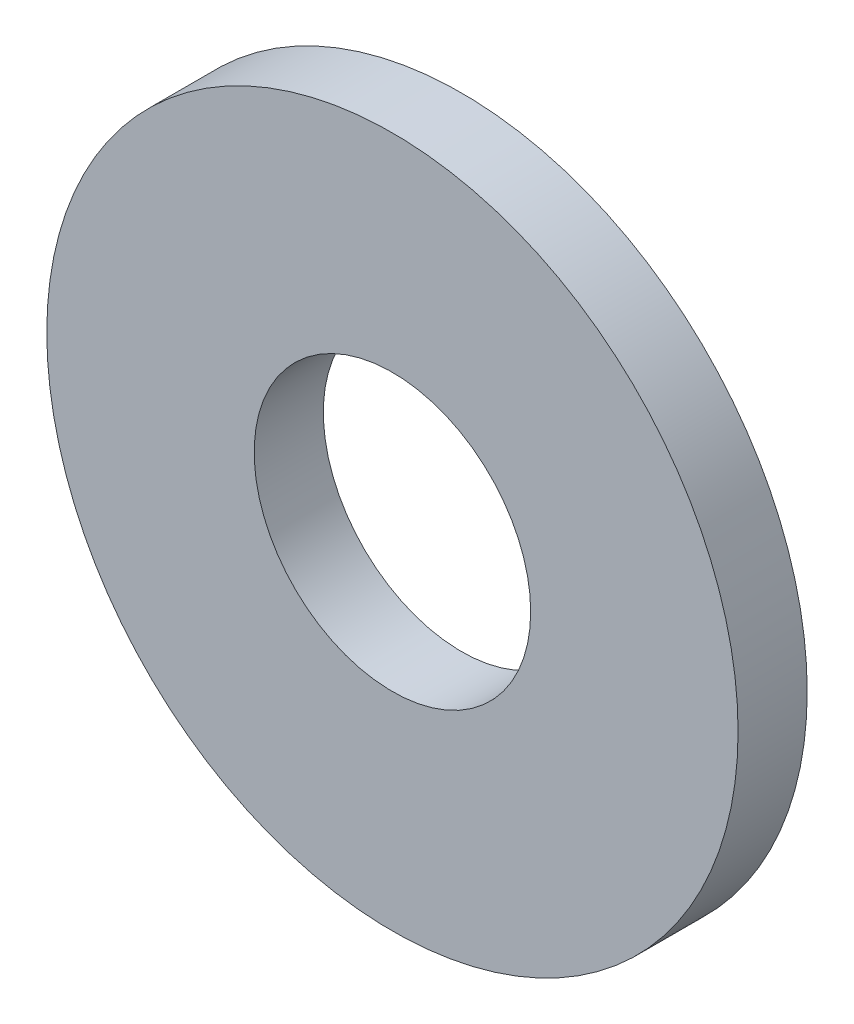
SolidWorks part; units mm, degrees
ref_plane "前视基准面" through (0, 0, 0) normal (0, 0, 1) x (1, 0, 0)
ref_plane "上视基准面" through (0, 0, 0) normal (0, 1, 0) x (1, 0, 0)
ref_plane "右视基准面" through (0, 0, 0) normal (1, 0, 0) x (0, 0, -1)
other "Configuration Table"
sketch "草图1" plane through (0, 0, 0) normal (0, 0, 1) x (1, 0, 0)
  circle A0 centre (0, 0) radius 1.6
  circle A1 centre (0, 0) radius 4
  dimension "D1" = 8
  dimension "D2" = 3.2
extrude "凸台-拉伸1" add sketch "草图1" along normal blind 0.8
